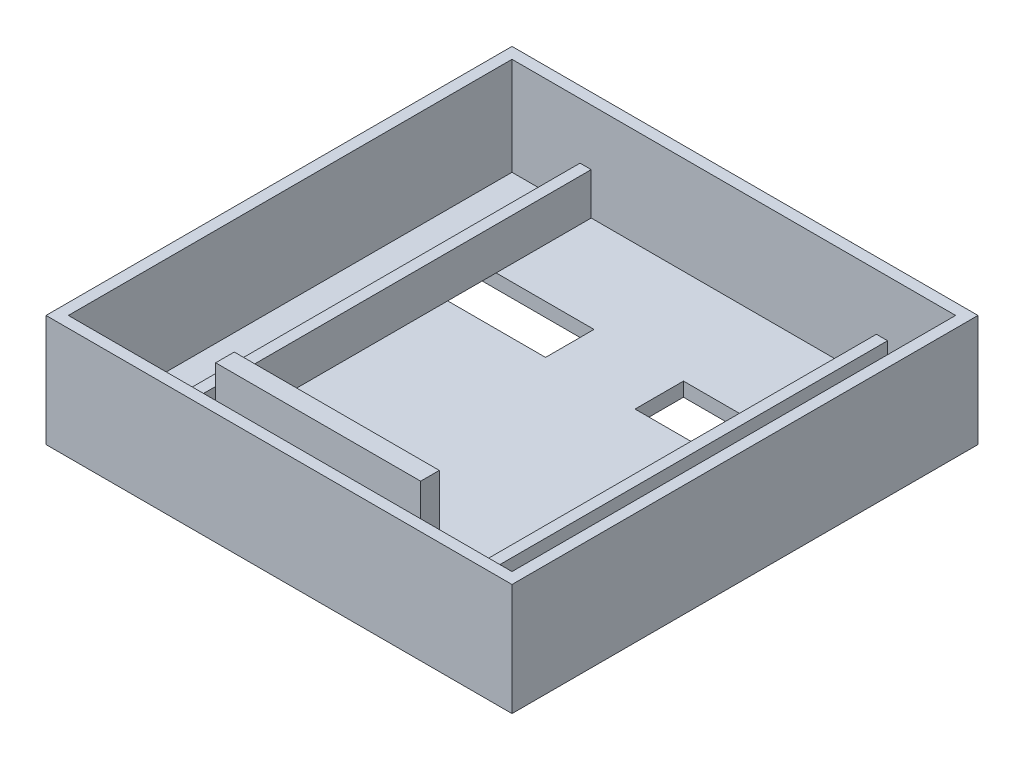
SolidWorks part; units mm, degrees
ref_plane "Alzado" through (0, 0, 0) normal (0, 0, 1) x (1, 0, 0)
ref_plane "Planta" through (0, 0, 0) normal (0, 1, 0) x (1, 0, 0)
ref_plane "Vista lateral" through (0, 0, 0) normal (1, 0, 0) x (0, 0, -1)
sketch "Croquis1" plane through (0, 0, 0) normal (0, 1, 0) x (1, 0, 0)
  line L1 (0, 0) -> (100, 0)
  line L2 (0, 0) -> (0, 100)
  line L3 (0, 100) -> (100, 100)
  line L4 (100, 0) -> (100, 100)
extrude "PlacaBase" add sketch "Croquis1" along normal blind 3
ref_plane "PL_SobreBase" through (0, 3, 0) normal (0, 1, 0) x (1, 0, 0)
sketch "Croquis2" plane through (0, 3, 0) normal (0, 1, 0) x (1, 0, 0)
  line L1 (0, 0) -> (100, 0)
  line L2 (0, 0) -> (0, 100)
  line L3 (0, 100) -> (100, 100)
  line L4 (100, 0) -> (100, 100)
  line L5 (2.4, 2.4) -> (97.6, 2.4)
  line L6 (2.4, 2.4) -> (2.4, 97.6)
  line L7 (2.4, 97.6) -> (97.6, 97.6)
  line L8 (97.6, 2.4) -> (97.6, 97.6)
extrude "Paredes" add sketch "Croquis2" along normal blind 21
sketch "RecortesRueda" plane through (0, 0, 0) normal (0, 1, 0) x (1, 0, 0)
  line L0 (0, 100) -> (0, 0) construction
  line L1 (0, 53) -> (14, 53)
  line L2 (0, 53) -> (0, 91)
  line L3 (0, 91) -> (14, 91)
  line L4 (14, 53) -> (14, 91)
  line L5 (100, 0) -> (100, 100) construction
  line L6 (86, 53) -> (100, 53)
  line L7 (86, 53) -> (86, 91)
  line L8 (86, 91) -> (100, 91)
  line L9 (100, 53) -> (100, 91)
ref_plane "PL_Motores" through (0, 7.3, 0) normal (0, 1, 0) x (1, 0, 0)
sketch "Croquis4" plane through (0, 7.3, 0) normal (0, 1, 0) x (1, 0, 0)
  line L0 (14, 53) -> (14, 91) construction
  line L1 (14, 66.8) -> (40.4, 66.8)
  line L2 (14, 66.8) -> (14, 77.2)
  line L3 (14, 77.2) -> (40.4, 77.2)
  line L4 (40.4, 66.8) -> (40.4, 77.2)
  line L5 (86, 53) -> (86, 91) construction
  line L6 (59.6, 66.8) -> (86, 66.8)
  line L7 (59.6, 66.8) -> (59.6, 77.2)
  line L8 (59.6, 77.2) -> (86, 77.2)
  line L9 (86, 66.8) -> (86, 77.2)
extrude "AlojamientosMotor" cut sketch "Croquis4" against normal blind 12.4
ref_plane "PL_Superior" through (0, 24, 0) normal (0, 1, 0) x (1, 0, 0)
sketch "BolsilloBateria" plane through (0, 24, 0) normal (0, 1, 0) x (1, 0, 0)
  line L1 (22, 26) -> (78, 26)
  line L2 (22, 26) -> (22, 57)
  line L3 (22, 57) -> (78, 57)
  line L4 (78, 26) -> (78, 57)
sketch "Croquis6" plane through (0, 3, 0) normal (0, 1, 0) x (1, 0, 0)
  line L0 (2.4, 2.4) -> (97.6, 2.4) construction
  line L1 (17, 2.4) -> (19.4, 2.4)
  line L2 (17, 2.4) -> (17, 97.6)
  line L3 (17, 97.6) -> (19.4, 97.6)
  line L4 (19.4, 2.4) -> (19.4, 97.6)
  line L5 (97.6, 97.6) -> (2.4, 97.6) construction
  line L7 (80.6, 2.4) -> (83, 2.4)
  line L8 (80.6, 2.4) -> (80.6, 97.6)
  line L9 (80.6, 97.6) -> (83, 97.6)
  line L10 (83, 2.4) -> (83, 97.6)
extrude "NerviosRigidez" add sketch "Croquis6" along normal blind 9
sketch "Croquis7" plane through (0, 3, 0) normal (0, 1, 0) x (1, 0, 0)
  line L0 (97.6, 2.4) -> (97.6, 97.6) construction
  line L1 (2.4, 2.4) -> (97.6, 2.4)
  line L2 (2.4, 2.4) -> (2.4, 8.4)
  line L3 (2.4, 8.4) -> (97.6, 8.4)
  line L4 (97.6, 2.4) -> (97.6, 8.4)
extrude "BloqueCuna" add sketch "Croquis7" along normal blind 10
sketch "Croquis8" plane through (0, 3, 0) normal (0, 1, 0) x (1, 0, 0)
  line L0 (80.6, 8.4) -> (19.4, 8.4) construction
  line L1 (28, 8.4) -> (72, 8.4)
  line L2 (28, 8.4) -> (28, 12.4)
  line L3 (28, 12.4) -> (72, 12.4)
  line L4 (72, 8.4) -> (72, 12.4)
extrude "TorreSensores" add sketch "Croquis8" along normal blind 22
sketch "VentanasSensoresLinea" plane through (0, 0, 0) normal (0, 1, 0) x (1, 0, 0)
  circle A0 centre (26, 24) radius 5
  circle A1 centre (74, 24) radius 5
  circle A2 centre (26, 94) radius 5
  circle A3 centre (74, 94) radius 5
sketch "AnclajesInsertos" plane through (0, 0, 0) normal (0, 1, 0) x (1, 0, 0)
  circle A0 centre (40, 62) radius 2.1
  circle A1 centre (60, 62) radius 2.1
  circle A2 centre (40, 82) radius 2.1
  circle A3 centre (60, 82) radius 2.1
  circle A4 centre (12, 16) radius 2.1
  circle A5 centre (88, 16) radius 2.1
equation "\"ANCHO\" = 100"
equation "\"PROF\" = 100"
equation "\"ALT\" = 24"
equation "\"BASE_T\" = 3"
equation "\"PARED\" = 2.4"
equation "\"EJE_Y\" = 72"
equation "\"EJE_Z\" = 13.5"
equation "\"RUEDA_D\" = 35"
equation "\"RUEDA_W\" = 12"
equation "\"MOT_L\" = 26"
equation "\"AJUSTE\" = 0.4"
